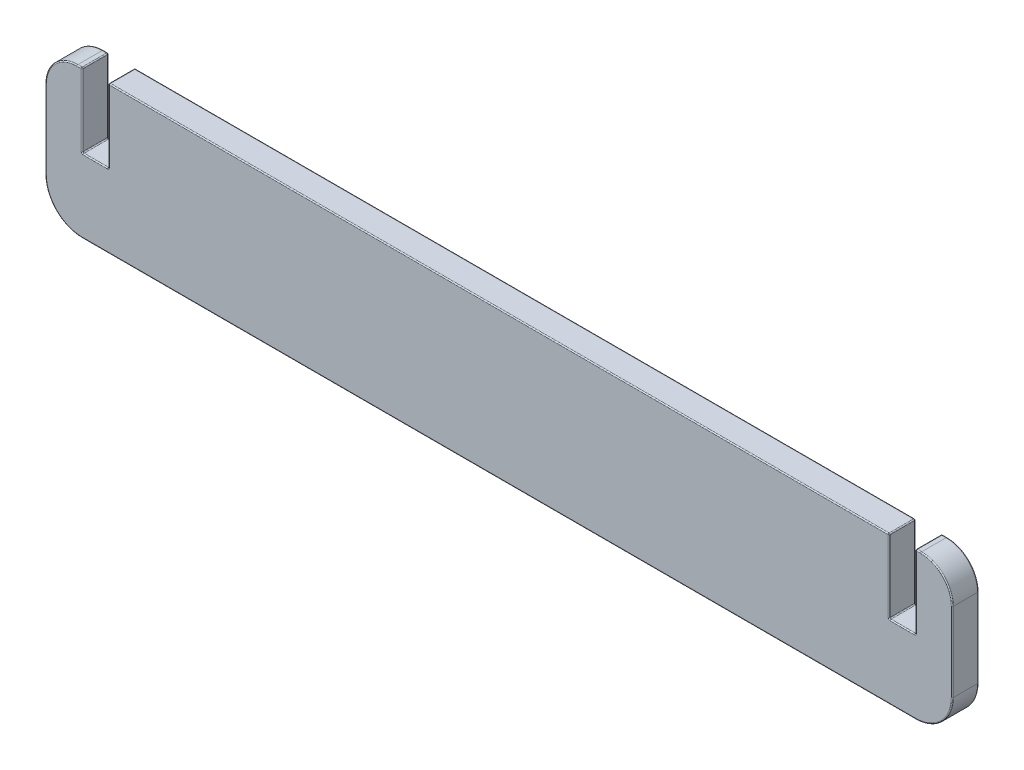
SolidWorks part; units mm, degrees
ref_plane "Plano frontal" through (0, 0, 0) normal (0, 0, 1) x (1, 0, 0)
ref_plane "Plano superior" through (0, 0, 0) normal (0, 1, 0) x (1, 0, 0)
ref_plane "Plano direito" through (0, 0, 0) normal (1, 0, 0) x (0, 0, -1)
sketch "Esboço1" plane through (0, 0, 0) normal (0, 0, 1) x (1, 0, 0)
  line L0 (-195.7976, 69.0191) -> (-116.5976, 69.0191)
  line L1 (-195.7976, 93.1191) -> (-195.7976, 86.3191)
  line L2 (-193.2976, 93.1191) -> (-193.2976, 86.3191)
  line L3 (-199.2976, 72.5188) -> (-199.2976, 119.0191) construction
  line L4 (-193.2976, 76.0191) -> (-195.7976, 76.0191)
  line L5 (-174.2976, 64.0191) -> (-174.2976, 119.0618) construction
  line L6 (-195.7976, 76.0191) -> (-195.7976, 83.0191)
  line L7 (-193.2976, 76.0191) -> (-193.2976, 83.0191)
  line L8 (-116.5976, 76.0191) -> (-116.5976, 83.0191)
  line L9 (-156.1976, 131.9283) -> (-156.1976, 54.9849) construction
  line L10 (-141.0976, 83.0191) -> (-141.0976, 112.5191) construction
  line L11 (-113.0976, 112.5191) -> (-199.2976, 112.5191)
  line L12 (-135.0976, 112.5191) -> (-135.0976, 83.0191) construction
  line L13 (-113.0976, 103.2191) -> (-199.2976, 103.2191)
  line L14 (-138.0976, 64.0191) -> (-138.0976, 119.0618) construction
  line L15 (-116.0976, 86.3191) -> (-196.2976, 86.3191)
  line L16 (-113.0976, 72.5188) -> (-113.0976, 119.0191) construction
  line L17 (-141.0976, 83.0191) -> (-141.0976, 86.3191)
  line L18 (-135.0976, 86.3191) -> (-141.0976, 86.3191)
  line L19 (-135.0976, 83.0191) -> (-135.0976, 86.3191)
  line L20 (-135.0976, 83.0191) -> (-141.0976, 83.0191)
  line L21 (-141.0976, 103.2191) -> (-141.0976, 99.9191)
  line L22 (-135.0976, 99.9191) -> (-141.0976, 99.9191)
  line L23 (-135.0976, 103.2191) -> (-135.0976, 99.9191)
  line L24 (-135.0976, 103.2191) -> (-141.0976, 103.2191)
  line L25 (-141.0976, 112.5191) -> (-141.0976, 109.2191)
  line L26 (-135.0976, 109.2191) -> (-141.0976, 109.2191)
  line L27 (-135.0976, 112.5191) -> (-135.0976, 109.2191)
  line L28 (-135.0976, 112.5191) -> (-141.0976, 112.5191)
  line L29 (-119.0976, 93.1191) -> (-116.5976, 93.1191)
  line L30 (-113.0976, 109.2191) -> (-113.0976, 103.2191)
  line L31 (-113.0976, 119.0191) -> (-113.0976, 112.5191)
  line L32 (-113.0976, 89.3191) -> (-113.0976, 96.9191)
  line L33 (-113.0976, 80.0191) -> (-113.0976, 72.5188)
  line L34 (-119.0976, 76.0191) -> (-119.0976, 83.0191)
  line L36 (-196.2976, 83.0191) -> (-116.0976, 83.0191)
  line L37 (-199.2976, 80.0191) -> (-199.2976, 72.5188)
  line L39 (-119.0976, 76.0191) -> (-116.5976, 76.0191)
  line L40 (-119.0976, 93.1191) -> (-119.0976, 86.3191)
  line L41 (-116.5976, 93.1191) -> (-116.5976, 86.3191)
  line L58 (-199.2976, 119.0191) -> (-113.0976, 119.0191)
  line L61 (-199.2976, 89.3191) -> (-199.2976, 96.9191)
  line L62 (-196.2976, 99.9191) -> (-116.0976, 99.9191)
  line L64 (-199.2976, 109.2191) -> (-113.0976, 109.2191)
  line L66 (-199.2976, 119.0191) -> (-199.2976, 112.5191)
  line L67 (-199.2976, 109.2191) -> (-199.2976, 103.2191)
  line L71 (-177.2976, 112.5191) -> (-177.2976, 83.0191) construction
  line L72 (-193.2976, 93.1191) -> (-195.7976, 93.1191)
  line L76 (-171.2976, 83.0191) -> (-171.2976, 112.5191) construction
  line L80 (-177.2976, 112.5191) -> (-171.2976, 112.5191)
  line L81 (-177.2976, 112.5191) -> (-177.2976, 109.2191)
  line L82 (-177.2976, 109.2191) -> (-171.2976, 109.2191)
  line L83 (-171.2976, 112.5191) -> (-171.2976, 109.2191)
  line L84 (-177.2976, 103.2191) -> (-171.2976, 103.2191)
  line L85 (-177.2976, 103.2191) -> (-177.2976, 99.9191)
  line L86 (-177.2976, 99.9191) -> (-171.2976, 99.9191)
  line L87 (-171.2976, 103.2191) -> (-171.2976, 99.9191)
  line L88 (-177.2976, 83.0191) -> (-171.2976, 83.0191)
  line L89 (-177.2976, 83.0191) -> (-177.2976, 86.3191)
  line L90 (-177.2976, 86.3191) -> (-171.2976, 86.3191)
  line L91 (-171.2976, 83.0191) -> (-171.2976, 86.3191)
  arc A0 (-116.0976, 86.3191) -> (-113.0976, 89.3191) centre (-116.0976, 89.3191) ccw
  arc A1 (-113.0976, 96.9191) -> (-116.0976, 99.9191) centre (-116.0976, 96.9191) ccw
  arc A2 (-116.0976, 83.0191) -> (-113.0976, 80.0191) centre (-116.0976, 80.0191) cw
  arc A3 (-116.5976, 69.0191) -> (-113.0976, 72.5188) centre (-116.5973, 72.5188) ccw
  arc A6 (-195.7976, 69.0191) -> (-199.2976, 72.5188) centre (-195.798, 72.5188) cw
  arc A7 (-196.2976, 83.0191) -> (-199.2976, 80.0191) centre (-196.2976, 80.0191) ccw
  arc A10 (-199.2976, 96.9191) -> (-196.2976, 99.9191) centre (-196.2976, 96.9191) cw
  arc A11 (-196.2976, 86.3191) -> (-199.2976, 89.3191) centre (-196.2976, 89.3191) cw
  point P8 (-156.1976, 83.0191)
  point P10 (-156.1976, 99.9191)
  point P11 (-156.1976, 112.5191)
  point P12 (-156.1976, 119.0191)
  point P13 (-156.1976, 103.2191)
  point P14 (-156.1976, 86.3191)
  point P48 (-156.1976, 109.2191)
  point P54 (-156.1976, 69.0191)
  dimension "D1" = 37.1
  dimension "D5" = 25
  dimension "D29" = 3
  dimension "D39" = 2.5
  dimension "D43" = 3
  dimension "D44" = 3
extrude "Ressalto-extrusão1" add sketch "Esboço1" along normal blind 2.5 contours L36 A7 L37 A6 L0 A3 L33 A2 L8 L39 L34 L20 L7 L4 L6
fillet "Filete1" radius 0.1 40 edges at (-116.5976, 83.0191, 1.25) (-116.5976, 76.0191, 1.25) (-119.0976, 76.0191, 1.25) (-119.0976, 83.0191, 1.25) (-193.2976, 83.0191, 1.25) (-193.2976, 76.0191, 1.25) (-195.7976, 76.0191, 1.25) (-195.7976, 83.0191, 1.25) (-195.7976, 79.5191, 2.5) (-194.5476, 76.0191, 2.5) (-193.2976, 79.5191, 2.5) (-156.1976, 83.0191, 2.5) (-119.0976, 79.5191, 2.5) (-117.8476, 76.0191, 2.5) (-116.5976, 79.5191, 2.5) (-116.3476, 83.0191, 2.5) (-113.9763, 82.1405, 2.5) (-113.0976, 76.269, 2.5) (-114.1228, 70.044, 2.5) (-156.1976, 69.0191, 2.5) (-198.2725, 70.044, 2.5) (-199.2976, 76.269, 2.5) (-198.419, 82.1405, 2.5) (-196.0476, 83.0191, 2.5) (-198.419, 82.1405, 0) (-199.2976, 76.269, 0) (-198.2725, 70.044, 0) (-156.1976, 69.0191, 0) (-114.1228, 70.044, 0) (-113.0976, 76.269, 0) (-113.9763, 82.1405, 0) (-116.3476, 83.0191, 0) (-116.5976, 79.5191, 0) (-117.8476, 76.0191, 0) (-119.0976, 79.5191, 0) (-156.1976, 83.0191, 0) (-193.2976, 79.5191, 0) (-194.5476, 76.0191, 0) (-195.7976, 79.5191, 0) (-196.0476, 83.0191, 0)
